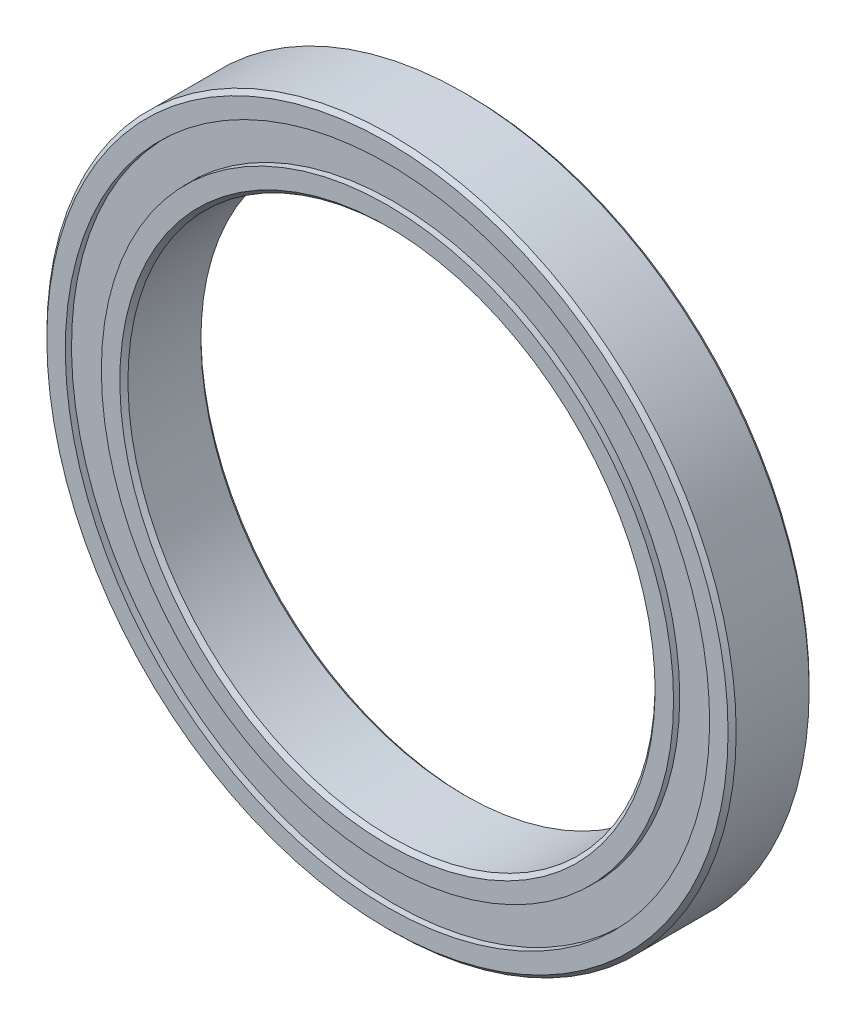
SolidWorks part; units mm, degrees
ref_plane "Front Plane" through (0, 0, 0) normal (0, 0, 1) x (1, 0, 0)
ref_plane "Top Plane" through (0, 0, 0) normal (0, 1, 0) x (1, 0, 0)
ref_plane "Right Plane" through (0, 0, 0) normal (1, 0, 0) x (0, 0, -1)
sketch "Sketch1" plane through (0, 0, 0) normal (0, 0, 1) x (1, 0, 0)
  circle A0 centre (0, 0) radius 42.5
  circle A1 centre (0, 0) radius 32.5
  dimension "OD" = 85
  dimension "ID" = 65
  dimension "For Shaft Diameter" = 65
  dimension "For Housing ID" = 85
sketch "Sketch8" plane through (0, 0, 0) normal (1, 0, 0) x (0, 0, -1)
  line L1 (-5, 42.5) -> (5, 42.5)
  line L2 (-5, 42.5) -> (-5, -42.5)
  line L3 (-5, -42.5) -> (5, -42.5)
  line L4 (5, 42.5) -> (5, -42.5)
  line L5 (-5, 42.5) -> (5, -42.5) construction
  line L6 (-5, -42.5) -> (5, 42.5) construction
  point P0 (0, 0)
  point P6 (0, -42.5)
  dimension "Width" = 10
sketch "Sketch5" plane through (0, 0, 0) normal (1, 0, 0) x (0, 0, -1)
  line L0 (-5, 0) -> (5, 0) construction
  line L1 (0, 42.5) -> (0, -42.5) construction
  line L2 (4.5, 42.5) -> (-4.5, 42.5)
  line L3 (-4.5, 42.5) -> (-5, 42)
  line L4 (-5, 42) -> (-5, 39.7222)
  line L5 (-5, 39.7222) -> (-2.2222, 39.7222)
  line L6 (5, 39.7222) -> (2.2222, 39.7222)
  line L7 (5, 42) -> (5, 39.7222)
  line L8 (4.5, 42.5) -> (5, 42)
  line L9 (0, 42.5) -> (0, 37.5) construction
  line L10 (0, 37.5) -> (0, 32.5) construction
  line L11 (-3.1427, 37.5) -> (-5, 37.5) construction
  line L12 (3.8808, 35.3032) -> (4.2618, 35.3032)
  line L13 (-3.8808, 35.3032) -> (-4.2618, 35.3032)
  line L14 (-3.8808, 35.3032) -> (-3.8808, 39.6968)
  line L15 (-3.8808, 39.6968) -> (-4.2618, 39.6968)
  line L16 (-4.2618, 35.3032) -> (-4.2618, 39.6968)
  line L17 (-3.8808, 35.3032) -> (-4.2618, 39.6968) construction
  line L18 (-3.8808, 39.6968) -> (-4.2618, 35.3032) construction
  line L19 (4.2618, 35.3032) -> (4.2618, 39.6968)
  line L20 (3.8808, 39.6968) -> (4.2618, 39.6968)
  line L21 (3.8808, 35.3032) -> (3.8808, 39.6968)
  line L22 (0, 42.5) -> (0, -42.5) construction
  line L23 (5, 0) -> (5, 42.5) construction
  line L24 (5, 42.5) -> (4.5, 42.5) construction
  line L25 (-5, 0) -> (-5, 42.5) construction
  line L26 (-5, 42.5) -> (-4.5, 42.5) construction
  line L27 (5, 0) -> (5, -42.5) construction
  line L28 (-5, 0) -> (-5, -42.5) construction
  line L29 (-5, -42.5) -> (5, -42.5) construction
  arc A0 (-2.2222, 39.7222) -> (2.2222, 39.7222) centre (0, 37.5) cw
  circle A1 centre (0, 37.5) radius 3.1427 construction
  point P14 (0, 32.5)
  point P15 (-4.0713, 37.5)
  dimension "D1" = 45
  dimension "D2" = 0.5
  dimension "D3" = 4.4444
  dimension "D4" = 2.2222
  dimension "D5" = 0.381
  dimension "D6" = 0.0254
revolve "Revolve1" add sketch "Sketch5" angle 360 about L0
sketch "Sketch3" plane through (0, 0, 0) normal (1, 0, 0) x (0, 0, -1)
  line L0 (-5, 35.2778) -> (-2.2222, 35.2778)
  line L1 (0, 42.5) -> (0, -42.5) construction
  line L2 (-5, 42) -> (-5, 39.7222) construction
  line L3 (-5, 35.2778) -> (-5, 33)
  line L4 (-4.5, 42.5) -> (-5, 42) construction
  line L5 (-5, 33) -> (-4.5, 32.5)
  line L6 (-4.5, 32.5) -> (4.5, 32.5)
  line L7 (4.5, 42.5) -> (4.5, -42.5) construction
  line L8 (4.5, 32.5) -> (5, 33)
  line L9 (5, -42) -> (5, 42) construction
  line L10 (5, 33) -> (5, 35.2778)
  line L11 (5, 35.2778) -> (2.2222, 35.2778)
  line L13 (4.5, 42.5) -> (5, 42) construction
  arc A0 (2.2222, 39.7222) -> (-2.2222, 39.7222) centre (0, 37.5) ccw construction
  arc A1 (2.2222, 35.2778) -> (-2.2222, 35.2778) centre (0, 37.5) cw
revolve "Revolve3" add sketch "Sketch3" angle 360 about L0
sketch "Sketch4" plane through (0, 0, 0) normal (1, 0, 0) x (0, 0, -1)
  line L0 (-3.1427, 37.5) -> (3.1427, 37.5)
  arc A2 (-3.1427, 37.5) -> (3.1427, 37.5) centre (0, 37.5) cw
  arc A3 (2.2222, 39.7222) -> (-2.2222, 39.7222) centre (0, 37.5) ccw construction
revolve "Revolve4" add sketch "Sketch4" angle 360 about L0
pattern_circular "CirPattern1" count 23 every 15.652 about axis through (0, 0, 0) along (0, 0, 1) of bodies 104
equation "\"D2@Sketch5\" = \"Width@Sketch8\" * .05"
equation "\"D3@Sketch5\" = \"Width@Sketch8\" / 2.25"
equation "\"D4@Sketch5\"=((\"OD@Sketch1\"-\"ID@Sketch1\")/2)/4.5"
equation "\"D2@CirPattern1\" = 360/\"Balls@CirPattern1\""
